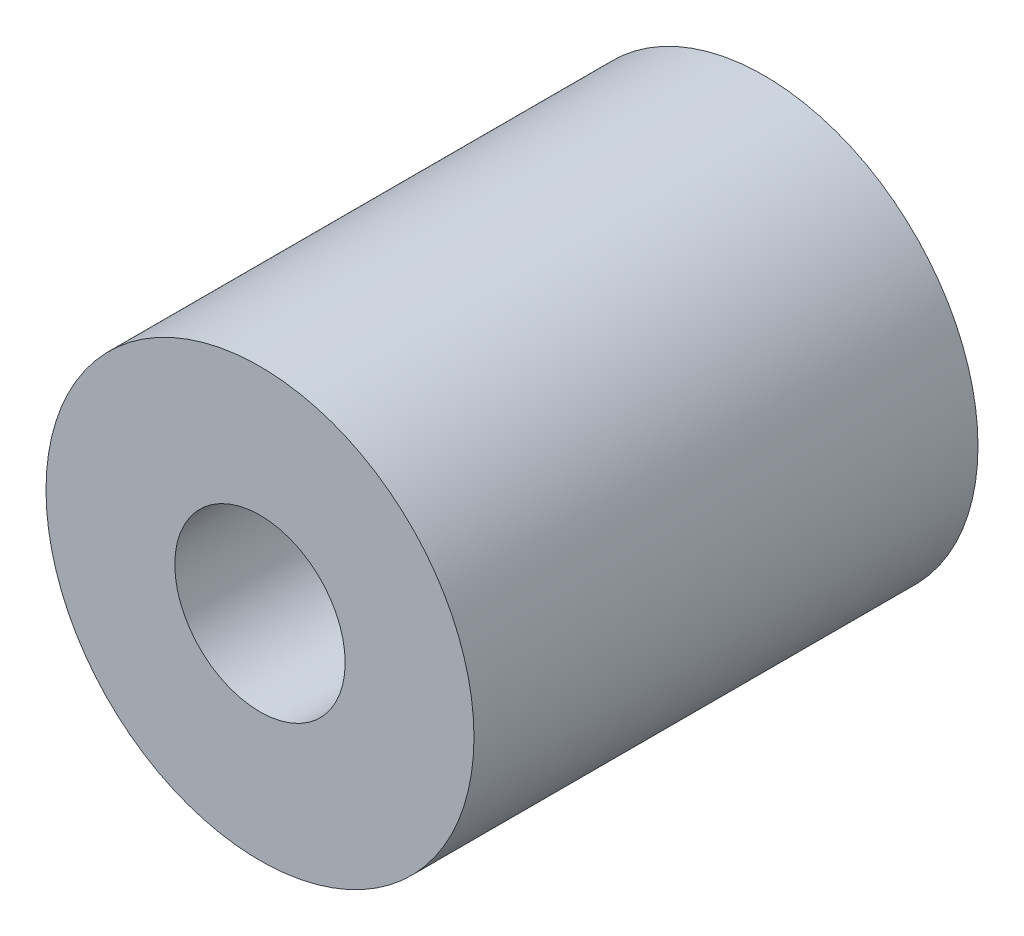
SolidWorks part; units mm, degrees
ref_plane "Alzado" through (0, 0, 0) normal (0, 0, 1) x (1, 0, 0)
ref_plane "Planta" through (0, 0, 0) normal (0, 1, 0) x (1, 0, 0)
ref_plane "Vista lateral" through (0, 0, 0) normal (1, 0, 0) x (0, 0, -1)
sketch "Croquis1" plane through (0, 0, 0) normal (0, 0, 1) x (1, 0, 0)
  circle A0 centre (0, 0) radius 1.9844
  circle A1 centre (0, 0) radius 4.9844
  dimension "D1" = 3.9688
  dimension "D2" = 3
extrude "Saliente-Extruir1" add sketch "Croquis1" along normal blind 11.74
